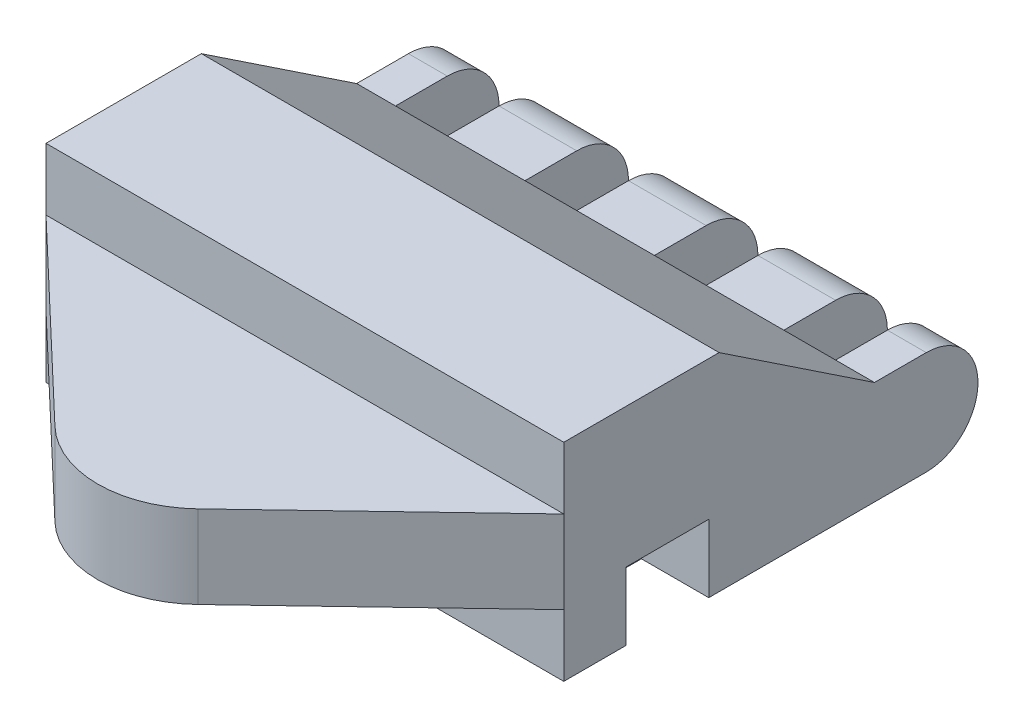
SolidWorks part; units mm, degrees
ref_plane "前视基准面" through (0, 0, 0) normal (0, 0, 1) x (1, 0, 0)
ref_plane "上视基准面" through (0, 0, 0) normal (0, 1, 0) x (1, 0, 0)
ref_plane "右视基准面" through (0, 0, 0) normal (1, 0, 0) x (0, 0, -1)
sketch "草图1" plane through (0, 0, 0) normal (0, 1, 0) x (1, 0, 0)
  line L0 (0, 0) -> (0, 89.2419) construction
  line L1 (0, 0) -> (89.3714, 0) construction
  line L2 (-50, 20) -> (-13.7931, -14.4828)
  line L4 (-50, 20) -> (-50, 80)
  line L5 (-50, 80) -> (50, 80)
  line L7 (50, 20) -> (13.7931, -14.4828)
  line L8 (50, 20) -> (50, 80)
  arc A0 (-13.7931, -14.4828) -> (13.7931, -14.4828) centre (0, 0) ccw
  dimension "D1" = 60
extrude "凸台-拉伸1" add sketch "草图1" along normal mid plane 40
sketch "草图2" plane through (0, 20, 0) normal (0, 1, 0) x (1, 0, 0)
  line L1 (-50, 20) -> (56.7364, 20)
  line L2 (-50, 20) -> (-50, -27.4294)
  line L3 (-50, -27.4294) -> (56.7364, -27.4294)
  line L4 (56.7364, 20) -> (56.7364, -27.4294)
extrude "切除-拉伸1" cut sketch "草图2" against normal blind 12
sketch "草图3" plane through (0, -20, 0) normal (0, -1, 0) x (1, 0, 0)
  line L1 (-50, -20) -> (52.6782, -20)
  line L2 (-50, -20) -> (-50, 26.4582)
  line L3 (-50, 26.4582) -> (52.6782, 26.4582)
  line L4 (52.6782, -20) -> (52.6782, 26.4582)
extrude "切除-拉伸2" cut sketch "草图3" against normal blind 12
sketch "草图4" plane through (50, 0, 0) normal (1, 0, 0) x (0, 0, -1)
  line L0 (80, 0) -> (50, 20)
  line L1 (80, 20) -> (80, -20) construction
  line L2 (20, 20) -> (80, 20) construction
  line L3 (50, 20) -> (88.6169, 20)
  line L4 (88.6169, 20) -> (88.6169, 0)
  line L5 (88.6169, 0) -> (80, 0)
extrude "切除-拉伸3" cut sketch "草图4" against normal through all
sketch "草图5" plane through (50, 0, 0) normal (1, 0, 0) x (0, 0, -1)
  line L0 (32, -20) -> (32, 21.7882) construction
  line L1 (20, -20) -> (80, -20) construction
  line L2 (32, -20) -> (32, 20.0369)
  dimension "D1" = 32
sketch3d "3D草图1"
  line L0 (50, -20, -32) -> (50, 20.0369, -32) construction
  line L1 (50, -20, -32) -> (50, 21.7882, -32) construction
  line L2 (37, -19.9107, -32) -> (23.6639, -19.9107, -32) construction
  line L3 (45, -14.9107, -32) -> (34.6278, -14.9107, -32) construction
  line L4 (37, -14.9107, -32) -> (37, -23.3419, -32)
  line L5 (37, -23.3419, -32) -> (45.3998, -22.9007, -32)
  line L6 (44.951, -6.9109, -32) -> (55.0075, -6.8493, -32)
  line L7 (55.0075, -6.8493, -32) -> (52.9989, -15.041, -32)
  arc A0 (45.3998, -22.9007, -32) -> (52.9989, -15.041, -32) centre (45, -14.9107, -32) ccw
  arc A1 (44.951, -6.9109, -32) -> (37, -14.9107, -32) centre (45, -14.9107, -32) ccw
  point P4 (45, -14.9107, -24)
  point P8 (45, -14.9107, -24)
  dimension "D1" = 5
  dimension "D2" = 5
extrude "切除-拉伸4" cut sketch "3D草图1" along direction (0, 0, -1) on the side of the normal blind 16
sketch "草图6" plane through (-50, 0, 0) normal (-1, 0, 0) x (0, 0, 1)
  line L0 (-100, -10) -> (-80, -10) construction
  line L10 (-90, 0) -> (-80, 0)
  line L12 (-90, -20) -> (-80, -20)
  line L13 (-80, 0) -> (-80, -20)
  arc A0 (-90, 0) -> (-90, -20) centre (-90, -10) ccw
sketch "草图8" plane through (0, -20, 0) normal (0, -1, 0) x (1, 0, 0)
  line L0 (50, -80) -> (-50, -80) construction
  line L1 (-50, -80) -> (-25, -80) construction
  line L2 (-25, -80) -> (0, -80) construction
  line L4 (-42.5, -80) -> (-32.5, -80)
  line L5 (-42.5, -80) -> (-42.5, -100)
  line L6 (-42.5, -100) -> (-32.5, -100)
  line L7 (-32.5, -80) -> (-32.5, -100)
  line L8 (-17.5, -80) -> (-7.5, -80)
  line L9 (-17.5, -80) -> (-17.5, -100)
  line L10 (-17.5, -100) -> (-7.5, -100)
  line L11 (-7.5, -80) -> (-7.5, -100)
  line L12 (7.5, -80) -> (17.5, -80)
  line L13 (7.5, -80) -> (7.5, -100)
  line L14 (7.5, -100) -> (17.5, -100)
  line L15 (17.5, -80) -> (17.5, -100)
  line L16 (32.5, -80) -> (42.5, -80)
  line L17 (32.5, -80) -> (32.5, -100)
  line L18 (32.5, -100) -> (42.5, -100)
  line L19 (42.5, -80) -> (42.5, -100)
  point P0 (0, -80)
  point P1 (-25, -80)
  point P4 (25, -80)
  point P5 (0, -80)
  point P6 (-25, -80)
  point P10 (-37.5, -80)
  point P11 (-12.5, -80)
  point P13 (37.5, -80)
  point P15 (12.5, -80)
  dimension "D1" = 10
  dimension "D2" = 20
  dimension "D3" = 5
  dimension "D4" = 10
  dimension "D5" = 5
  dimension "D6" = 10
  dimension "D7" = 5
  dimension "D8" = 10
  dimension "D9" = 5
extrude "凸台-拉伸4" add sketch "草图6" against normal blind 100
extrude "切除-拉伸6" cut sketch "草图8" against normal blind 100
sketch "草图9" plane through (0, 0, -32) normal (0, 0, -1) x (-1, 0, 0)
  line L0 (50, 20) -> (50, -20) construction
  line L1 (50, -20) -> (-50, -20) construction
  line L2 (45, -7) -> (50, -7)
  line L3 (50, -7) -> (59.4596, -7)
  line L4 (59.4596, -7) -> (59.4596, -23)
  line L5 (59.4596, -23) -> (37, -23)
  line L6 (37, -23) -> (37, -15)
  arc A0 (45, -7) -> (37, -15) centre (45, -15) ccw
  dimension "D1" = 5
  dimension "D2" = 5
extrude "切除-拉伸7" cut sketch "草图9" along normal blind 16
